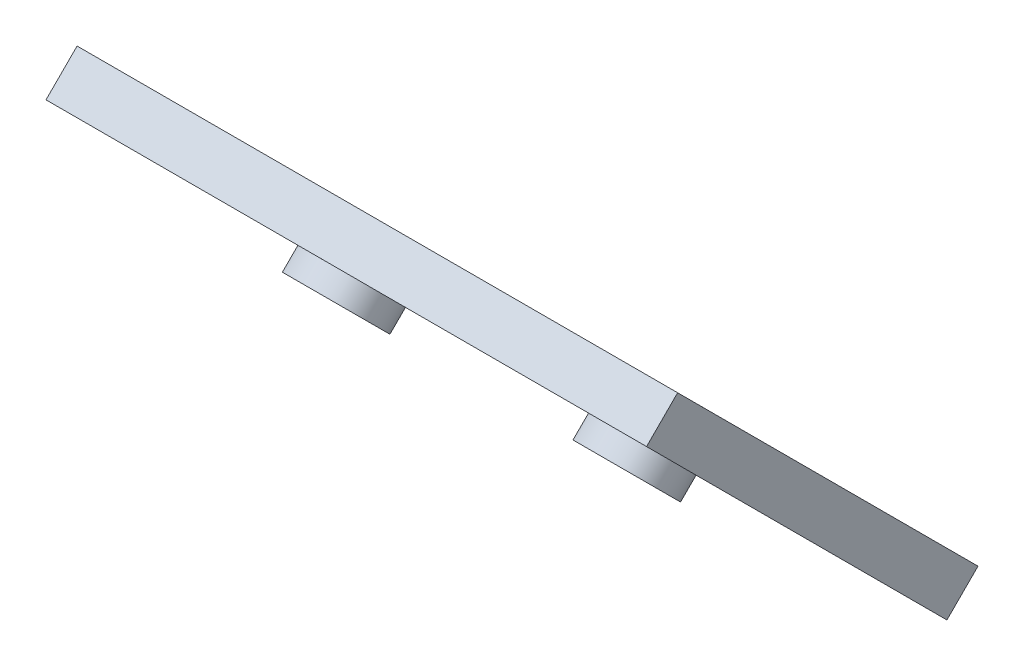
SolidWorks part; units mm, degrees
ref_plane "Front" through (0, 0, 0) normal (0, 0, 1) x (1, 0, 0)
ref_plane "Top" through (0, 0, 0) normal (0, 1, 0) x (1, 0, 0)
ref_plane "Right" through (0, 0, 0) normal (1, 0, 0) x (0, 0, -1)
sketch "Sketch1" plane through (0, 0, 0) normal (0, 0, 1) x (1, 0, 0)
  line L1 (-20.5, 14.5) -> (20.5, 14.5)
  line L2 (-20.5, 14.5) -> (-20.5, -14.5)
  line L3 (-20.5, -14.5) -> (20.5, -14.5)
  line L4 (20.5, 14.5) -> (20.5, -14.5)
  line L5 (-20.5, 14.5) -> (20.5, -14.5) construction
  line L6 (-20.5, -14.5) -> (20.5, 14.5) construction
  point P0 (0, 0)
  dimension "D1" = 41
  dimension "D2" = 29
extrude "Boss-Extrude1" add sketch "Sketch1" along normal blind 3
move or copy body "Body-Move/Copy1" bodies to move or copy 101 copy no translate (0.5, 0.5, 0)
sketch "Sketch11" plane through (0, 0, 3) normal (0, 0, 1) x (1, 0, 0)
  circle A0 centre (-9.3872, 0.5) radius 3
  circle A1 centre (10.4529, 0.5) radius 3
  point P0 (-9.3872, 0.5)
  point P1 (10.4529, 0.5)
  dimension "D1" = 6
  dimension "D2" = 6
extrude "Boss-Extrude2" add sketch "Sketch11" along normal blind 1.5
hole_wizard "Ø4.0 (4) Diameter Hole1" positions "Sketch14" profile "Sketch15" hole size "Ø4.0" standard "ANSI Metric" end condition up to next
sketch "Sketch14" plane through (0, 0, 4.5) normal (0, 0, 1) x (1, 0, 0)
  point P0 (-9.3872, 0.5)
  point P3 (10.4529, 0.5)
sketch "Sketch15" plane through (-9.3872, 0.5, 4.5) normal (1, 0, 0) x (0, -1, 0)
  line L0 (0, 0) -> (0, 4.5)
  line L1 (0, 4.5) -> (2, 4.5)
  line L2 (2, 4.5) -> (2, 0)
  line L5 (2, 0) -> (0, 0)
  line L11 (0, -6.35) -> (0, 107.95) construction
  dimension "Thru Hole Dia." = 4
  dimension "Thru Hole Depth" = 4.5
move or copy body "Body-Move/Copy8" bodies to move or copy 104 copy no translate (27.7957, 0, 0)
move or copy body "Body-Move/Copy9" bodies to move or copy 113 copy no rotation origin (0, 0.5, 2.25) rotation axis (1, 0, 0) rotation angle 45
